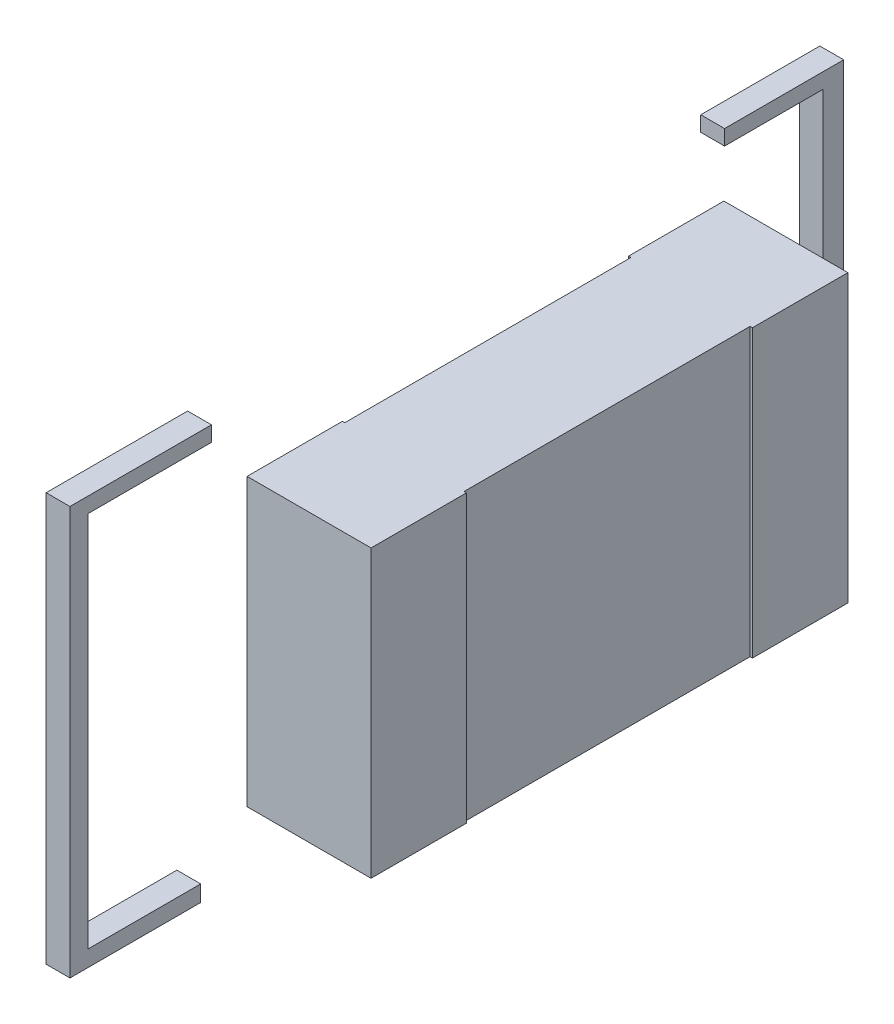
SolidWorks part; units mm, degrees
ref_plane "前视基准面" through (0, 0, 0) normal (0, 0, 1) x (1, 0, 0)
ref_plane "上视基准面" through (0, 0, 0) normal (0, 1, 0) x (1, 0, 0)
ref_plane "右视基准面" through (0, 0, 0) normal (1, 0, 0) x (0, 0, -1)
sketch "草图1" plane through (0, 0, 0) normal (1, 0, 0) x (0, 0, -1)
  line L1 (0, 0) -> (1.2, 0)
  line L2 (0, 0) -> (0, -1.2)
  line L3 (0, -1.2) -> (1.2, -1.2)
  line L4 (1.2, 0) -> (1.2, -1.2)
  dimension "D1" = 1.2
  dimension "D2" = 1.2
extrude "凸台-拉伸1" add sketch "草图1" along normal blind 0.5
sketch "草图2" plane through (0, 0, 0) normal (0, 0, 1) x (1, 0, 0)
  line L0 (0.25, 0.0537) -> (0.25, -1.3586) construction
  line L1 (-0.01, 0) -> (0.51, 0)
  line L2 (-0.01, 0) -> (-0.01, -1.2)
  line L3 (-0.01, -1.2) -> (0.51, -1.2)
  line L4 (0.51, 0) -> (0.51, -1.2)
  dimension "D1" = 0.26
  dimension "D2" = 0.26
  dimension "D3" = 1.2
extrude "凸台-拉伸3" add sketch "草图2" along normal blind 0.4
ref_plane "基准面1" through (0, 0, -0.6) normal (0, 0, 1) x (1, 0, 0)
mirror "镜向1" about plane through (0, 0, -0.6) normal (0, 0, 1) of "凸台-拉伸3"
sketch "草图3" plane through (-0.01, 0, 0) normal (-1, 0, 0) x (0, 0, 1)
  line L0 (-1.6029, 0.262) -> (-1.6029, 0.1982)
  line L1 (-2.1024, 0.262) -> (-1.6029, 0.262)
  line L2 (-2.1024, 0.262) -> (-2.1024, -1.4508)
  line L3 (-2.1024, -1.4508) -> (-1.6029, -1.4508)
  line L4 (1.1428, 0.262) -> (1.1428, -1.4508)
  line L5 (-2.0161, 0.1982) -> (-1.6029, 0.1982)
  line L6 (-2.0161, 0.1982) -> (-2.0161, -1.3832)
  line L7 (-2.0161, -1.3832) -> (-1.6029, -1.3832)
  line L8 (1.0677, 0.1982) -> (1.0677, -1.3832)
  line L9 (0.5944, -1.3832) -> (1.0677, -1.3832)
  line L10 (-1.6029, -1.3832) -> (-1.6029, -1.4508)
  line L11 (0.5944, -1.4508) -> (1.1428, -1.4508)
  line L12 (0.5944, -1.3832) -> (0.5944, -1.4508)
  line L13 (0.5494, 0.262) -> (0.5494, 0.1982)
  line L14 (0.5494, 0.1982) -> (1.0677, 0.1982)
  line L15 (0.5494, 0.262) -> (1.1428, 0.262)
extrude "凸台-拉伸4" add sketch "草图3" along normal blind 0.1 separate body
